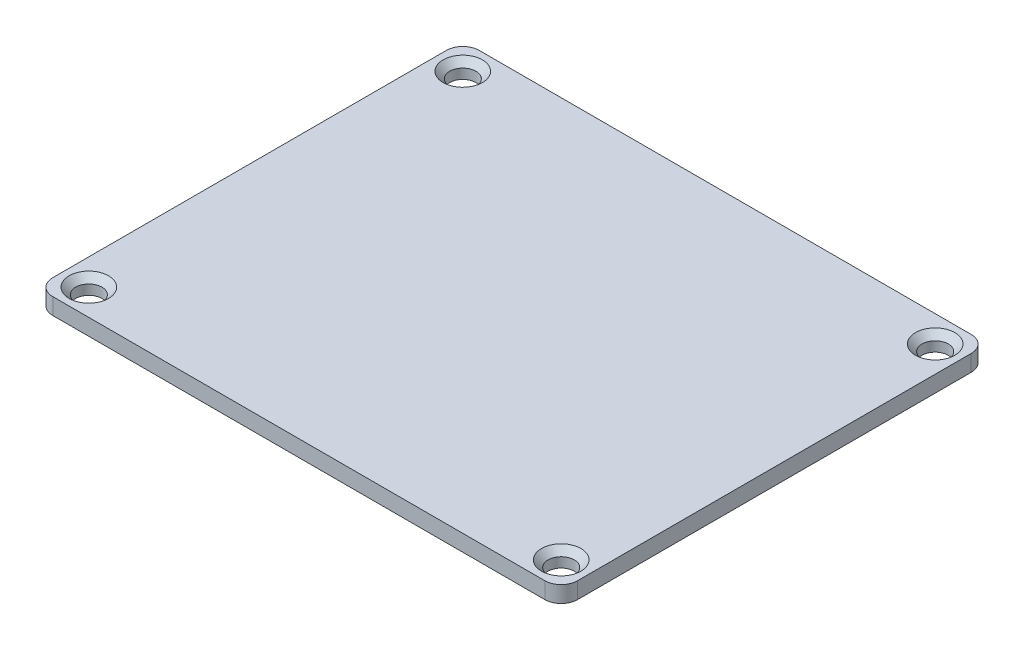
SolidWorks part; units mm, degrees
ref_plane "Alzado" through (0, 0, 0) normal (0, 0, 1) x (1, 0, 0)
ref_plane "Planta" through (0, 0, 0) normal (0, 1, 0) x (1, 0, 0)
ref_plane "Vista lateral" through (0, 0, 0) normal (1, 0, 0) x (0, 0, -1)
sketch "Croquis1" plane through (0, 0, 0) normal (0, 1, 0) x (1, 0, 0)
  line L1 (40, -32.5) -> (-40, -32.5)
  line L2 (40, -32.5) -> (40, 32.5)
  line L3 (40, 32.5) -> (-40, 32.5)
  line L4 (-40, -32.5) -> (-40, 32.5)
  line L5 (40, -32.5) -> (-40, 32.5) construction
  line L6 (40, 32.5) -> (-40, -32.5) construction
  point P0 (0, 0)
extrude "Saliente-Extruir1" add sketch "Croquis1" along normal blind 2.5
sketch "Croquis2" plane through (0, 2.5, 0) normal (0, 1, 0) x (1, 0, 0)
  line L0 (-34, 26.5) -> (-40, 32.5) construction
  line L1 (40, 32.5) -> (-40, 32.5) construction
  line L2 (-34, 32.5) -> (-34, 26.5) construction
  line L3 (-34, 26.5) -> (-40, 26.5) construction
  line L4 (-40, 32.5) -> (-40, -32.5) construction
  line L5 (-34, 26.5) -> (-34, 28.5) construction
  line L6 (-34, 28.5) -> (-36, 28.5) construction
  line L7 (-36, 28.5) -> (-36, 26.5) construction
  line L8 (0, -1.375) -> (0, 1.375) construction
  line L9 (36, 28.5) -> (36, 26.5) construction
  line L10 (34, 28.5) -> (36, 28.5) construction
  line L11 (34, 26.5) -> (34, 28.5) construction
  line L12 (34, 26.5) -> (40, 26.5) construction
  line L13 (34, 32.5) -> (34, 26.5) construction
  line L14 (34, 26.5) -> (40, 32.5) construction
  line L15 (-1.375, 0) -> (1.375, 0) construction
  line L16 (-36, -28.5) -> (-36, -26.5) construction
  line L17 (-34, -28.5) -> (-36, -28.5) construction
  line L18 (-34, -26.5) -> (-34, -28.5) construction
  line L19 (-34, -26.5) -> (-40, -26.5) construction
  line L20 (-34, -32.5) -> (-34, -26.5) construction
  line L21 (-34, -26.5) -> (-40, -32.5) construction
  line L22 (34, -26.5) -> (40, -32.5) construction
  line L23 (34, -32.5) -> (34, -26.5) construction
  line L24 (34, -26.5) -> (40, -26.5) construction
  line L25 (34, -26.5) -> (34, -28.5) construction
  line L26 (34, -28.5) -> (36, -28.5) construction
  line L27 (36, -28.5) -> (36, -26.5) construction
  circle A0 centre (-36, 28.5) radius 2
  circle A1 centre (36, 28.5) radius 2
  circle A2 centre (-36, -28.5) radius 2
  circle A3 centre (36, -28.5) radius 2
extrude "Cortar-Extruir1" cut sketch "Croquis2" against normal up to next
fillet "Redondeo1" radius 2.5 4 edges at (-40, 1.25, -32.5) (40, 1.25, -32.5) (40, 1.25, 32.5) (-40, 1.25, 32.5)
chamfer "Chaflán1" distance 1 angle 45 4 edges at (36, 2.5, -30.5) (36, 2.5, 30.5) (-36, 2.5, 26.5) (-36, 2.5, -26.5)
